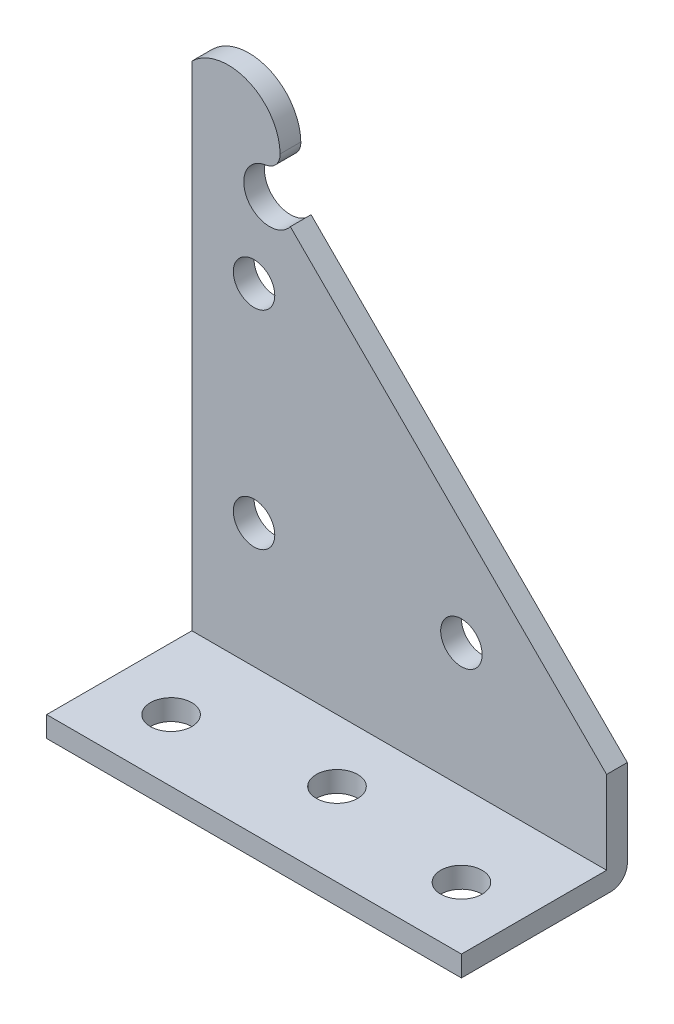
SolidWorks part; units mm, degrees
ref_plane "Front Plane" through (0, 0, 0) normal (0, 0, 1) x (1, 0, 0)
ref_plane "Top Plane" through (0, 0, 0) normal (0, 1, 0) x (1, 0, 0)
ref_plane "Right Plane" through (0, 0, 0) normal (1, 0, 0) x (0, 0, -1)
sketch "Sketch1" plane through (0, 0, 0) normal (0, 1, 0) x (1, 0, 0)
  line L0 (-31.75, 0) -> (31.75, 0) construction
  line L1 (31.75, -12.7) -> (-31.75, -12.7)
  line L2 (31.75, -12.7) -> (31.75, 12.7)
  line L3 (31.75, 12.7) -> (-31.75, 12.7)
  line L4 (-31.75, -12.7) -> (-31.75, 12.7)
  line L5 (31.75, -12.7) -> (-31.75, 12.7) construction
  line L6 (31.75, 12.7) -> (-31.75, -12.7) construction
  line L7 (0, -55) -> (0, 55) construction
  circle A0 centre (-22.225, -3.175) radius 3.175
  circle A1 centre (0, 0) radius 3.175
  circle A2 centre (22.225, -3.175) radius 3.175
  point P19 (0, 0)
  dimension "D1" = 9.525
  dimension "D2" = 9.525
  dimension "D3" = 31.75
  dimension "D4" = 25.4
extrude "Boss-Extrude1" add sketch "Sketch1" along normal blind 3.175
sketch "Sketch2" plane through (0, 0, -12.7) normal (0, 0, 1) x (1, 0, 0)
  line L0 (-31.75, 0) -> (-31.75, 78.7051)
  line L1 (31.75, 0) -> (31.75, 15.875)
  line L2 (31.75, 15.875) -> (-16.6697, 64.2947)
  line L3 (-31.75, 0) -> (31.75, 0) construction
  line L4 (-31.75, 3.175) -> (31.75, 3.175) construction
  line L7 (31.75, 3.175) -> (31.75, 0) construction
  line L8 (-31.75, 0) -> (31.75, 0)
  arc A0 (-31.75, 78.7051) -> (-18.2382, 73.1485) centre (-26.1874, 73.025) cw
  arc A1 (-18.2382, 73.1485) -> (-20.4105, 70.5957) centre (-20.7779, 73.109) cw
  circle A2 centre (-22.225, 53.975) radius 3.175
  circle A3 centre (-22.225, 22.225) radius 3.175
  circle A4 centre (9.525, 22.225) radius 3.175
  arc A5 (-20.4105, 70.5957) -> (-16.6697, 64.2947) centre (-19.8374, 66.675) ccw
  dimension "D3" = 7.9502
  dimension "D4" = 6.35
  dimension "D8" = 6.35
  dimension "D7" = 2.54
  dimension "D14" = 3.9624
  dimension "D1" = 5.5626
  dimension "D2" = 6.35
  dimension "D5" = 15.875
  dimension "D6" = 45
  dimension "D9" = 9.525
  dimension "D10" = 31.75
  dimension "D11" = 22.225
  dimension "D12" = 31.75
  dimension "D13" = 19.05
extrude "Boss-Extrude2" add sketch "Sketch2" along normal blind 3.175
fillet "Fillet2" radius 2.54 1 edges at (0, 0, -12.7)
